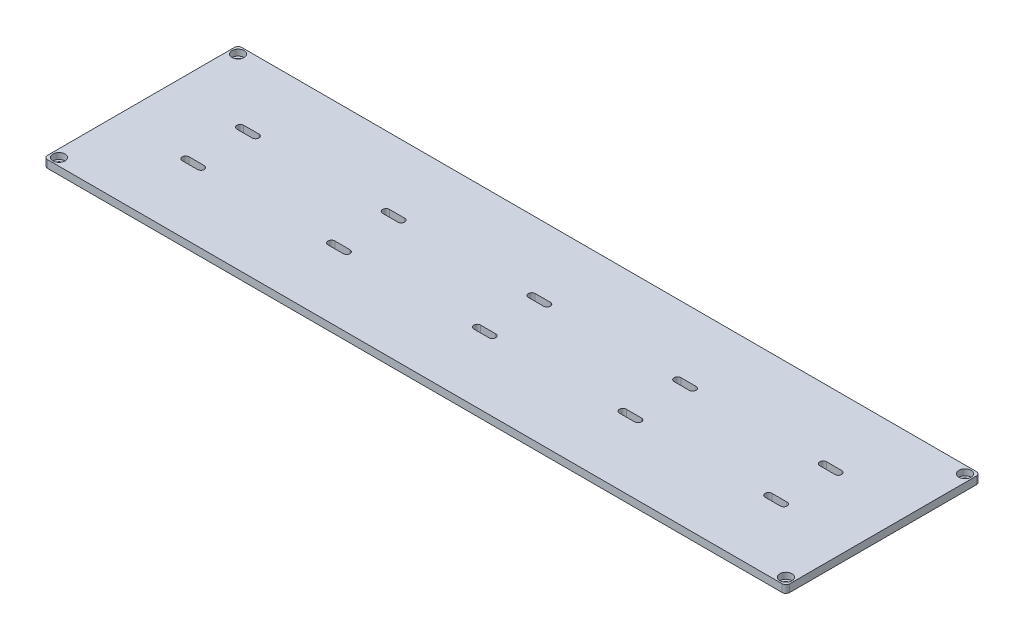
SolidWorks part; units mm, degrees
ref_plane "Front Plane" through (0, 0, 0) normal (0, 0, 1) x (1, 0, 0)
ref_plane "Top Plane" through (0, 0, 0) normal (0, 1, 0) x (1, 0, 0)
ref_plane "Right Plane" through (0, 0, 0) normal (1, 0, 0) x (0, 0, -1)
sketch "Sketch1" plane through (0, 0, 0) normal (0, 1, 0) x (1, 0, 0)
  line L1 (-244.475, 64) -> (244.475, 64)
  line L2 (-244.475, 64) -> (-244.475, -64)
  line L3 (-244.475, -64) -> (244.475, -64)
  line L4 (244.475, 64) -> (244.475, -64)
  line L5 (-244.475, 64) -> (244.475, -64) construction
  line L6 (-244.475, -64) -> (244.475, 64) construction
  point P0 (0, 0)
  dimension "D1" = 128
  dimension "D2" = 488.95
extrude "Boss-Extrude1" add sketch "Sketch1" along normal blind 5
hole_wizard "CBORE for M4 SHCS1" positions "Sketch2" profile "Sketch3" counterbore size "M4" standard "ANSI Metric"
sketch "Sketch2" plane through (0, 5, 0) normal (0, 1, 0) x (1, 0, 0)
  line L0 (239.475, 59) -> (239.475, -59) construction
  line L1 (239.475, -59) -> (-239.475, -59) construction
  line L2 (-239.475, -59) -> (-239.475, 59) construction
  line L3 (-239.475, 59) -> (239.475, 59) construction
  line L6 (-244.475, 64) -> (-244.475, -64) construction
  line L7 (244.475, 64) -> (-244.475, 64) construction
  line L8 (-244.475, -64) -> (244.475, -64) construction
  line L9 (244.475, -64) -> (244.475, 64) construction
  point P0 (-239.475, 59)
  point P2 (-239.475, -59)
  point P4 (239.475, -59)
  point P6 (239.475, 59)
  dimension "D1" = 5
  dimension "D2" = 5
  dimension "D3" = 5
  dimension "D4" = 5
sketch "Sketch3" plane through (-239.475, 5, -59) normal (1, 0, 0) x (0, 0, 1)
  line L0 (0, 0) -> (0, 18.7319)
  line L1 (0, 18.7319) -> (2.25, 17.38)
  line L2 (2.25, 17.38) -> (2.25, 4)
  line L3 (2.25, 4) -> (4, 4)
  line L4 (4, 4) -> (4, 0)
  line L5 (4, 0) -> (0, 0)
  line L10 (0, 18.7319) -> (-2.25, 17.38) construction
  line L11 (0, -6.35) -> (0, 107.95) construction
  dimension "Hole Dia." = 4.5
  dimension "Hole Depth" = 17.38
  dimension "C'Bore Dia." = 8
  dimension "C'Bore Depth" = 4
  dimension "Drill Angle" = 118
fillet "Fillet1" radius 2.5 4 edges at (244.475, 2.5, -64) (244.475, 2.5, 64) (-244.475, 2.5, -64) (-244.475, 2.5, 64)
sketch "Sketch4" plane through (0, 5, 0) normal (0, 1, 0) x (1, 0, 0)
  line L0 (-196.975, 18) -> (-186.975, 18) construction
  line L1 (-196.975, 20.25) -> (-186.975, 20.25)
  line L2 (-196.975, 15.75) -> (-186.975, 15.75)
  line L3 (-196.975, -18) -> (-186.975, -18) construction
  line L4 (-196.975, -15.75) -> (-186.975, -15.75)
  line L5 (-196.975, -20.25) -> (-186.975, -20.25)
  line L6 (-191.975, 18) -> (-191.975, -18) construction
  line L7 (-244.475, 61.5) -> (-244.475, -61.5) construction
  arc A0 (-196.975, 20.25) -> (-196.975, 15.75) centre (-196.975, 18) ccw
  arc A1 (-186.975, 15.75) -> (-186.975, 20.25) centre (-186.975, 18) ccw
  arc A2 (-196.975, -15.75) -> (-196.975, -20.25) centre (-196.975, -18) ccw
  arc A3 (-186.975, -20.25) -> (-186.975, -15.75) centre (-186.975, -18) ccw
  point P2 (-191.975, 18)
  point P7 (-191.975, -18)
  point P18 (-244.475, 0)
  point P19 (-191.975, 0)
  dimension "D1" = 10
  dimension "D2" = 4.5
  dimension "D3" = 4.5
  dimension "D4" = 10
  dimension "D5" = 36
  dimension "D6" = 52.5
extrude "Cut-Extrude1" cut sketch "Sketch4" against normal through all
pattern_linear "LPattern1" count 5 spacing 96 along (1, 0, 0) of "Cut-Extrude1"
